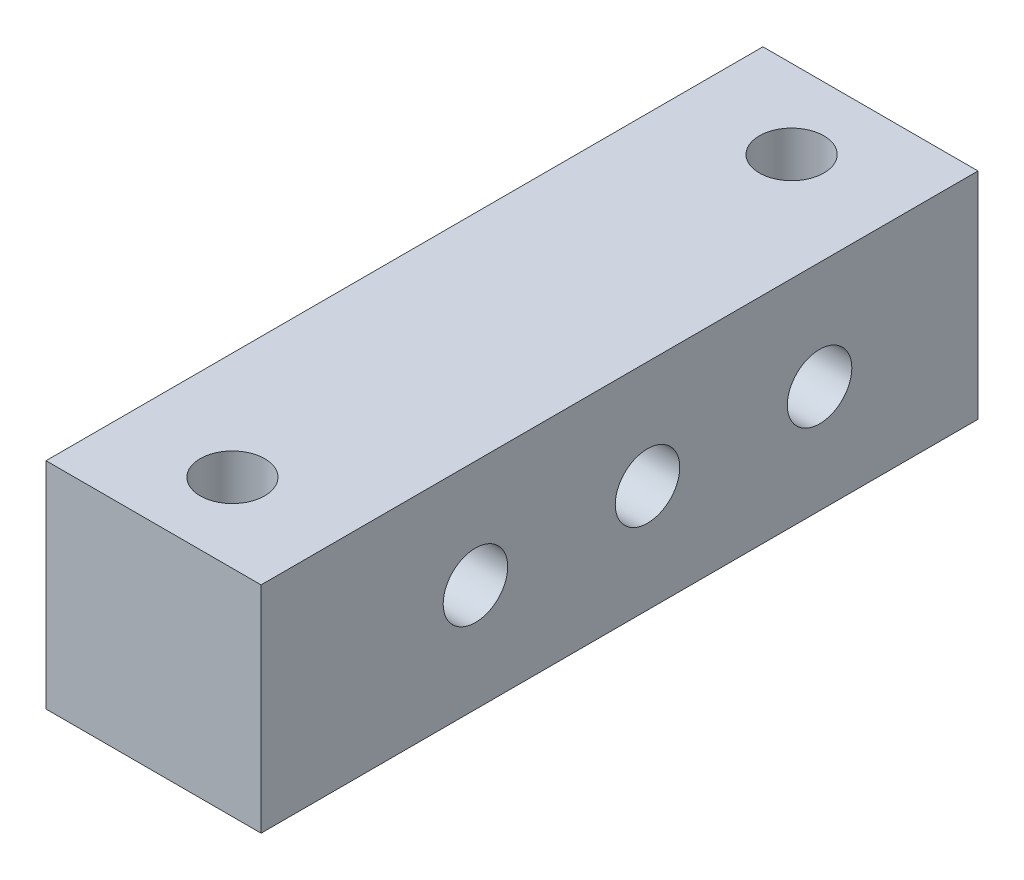
SolidWorks part; units mm, degrees
ref_plane "Plan de face" through (0, 0, 0) normal (0, 0, 1) x (1, 0, 0)
ref_plane "Plan de dessus" through (0, 0, 0) normal (0, 1, 0) x (1, 0, 0)
ref_plane "Plan de droite" through (0, 0, 0) normal (1, 0, 0) x (0, 0, -1)
sketch "Esquisse1" plane through (0, 0, 0) normal (0, 0, 1) x (1, 0, 0)
  line L1 (0, 0) -> (15, 0)
  line L2 (0, 0) -> (0, 15)
  line L3 (0, 15) -> (15, 15)
  line L4 (15, 0) -> (15, 15)
  dimension "D1" = 15
  dimension "D2" = 15
extrude "Boss.-Extru.1" add sketch "Esquisse1" along normal blind 50
sketch "Esquisse2" plane through (0, 15, 0) normal (0, 1, 0) x (1, 0, 0)
  line L0 (7.5, -44.5) -> (7.5, -5.5) construction
  line L1 (7.5, -25) -> (0, -25) construction
  line L2 (0, -50) -> (0, 0) construction
  line L3 (7.5, -44.5) -> (7.5, -50) construction
  line L4 (15, -50) -> (0, -50) construction
  circle A0 centre (7.5, -44.5) radius 2.25
  circle A1 centre (7.5, -5.5) radius 2.25
  dimension "D2" = 4.5
  dimension "D1" = 39
extrude "Enlèv. mat.-Extru.1" cut sketch "Esquisse2" against normal through all
sketch "Esquisse3" plane through (0, 0, 0) normal (-1, 0, 0) x (0, 0, 1)
  line L0 (0, 7.5) -> (50, 7.5) construction
  line L1 (0, 15) -> (0, 0) construction
  line L2 (50, 15) -> (50, 0) construction
  line L3 (23.05, 7.5) -> (23.05, 0) construction
  line L5 (50, 0) -> (0, 0) construction
  circle A0 centre (23.05, 7.5) radius 2.25
  circle A1 centre (35.05, 7.5) radius 2.25
  circle A2 centre (11.05, 7.5) radius 2.25
  point P6 (22.9319, 7.5)
  point P12 (23.0437, 0)
  point P16 (0, 0)
  point P18 (0, 0)
  point P19 (23.0437, 7.5)
  dimension "D1" = 4.5
  dimension "D2" = 12
  dimension "D3" = 26.95
extrude "Enlèv. mat.-Extru.2" cut sketch "Esquisse3" against normal through all
